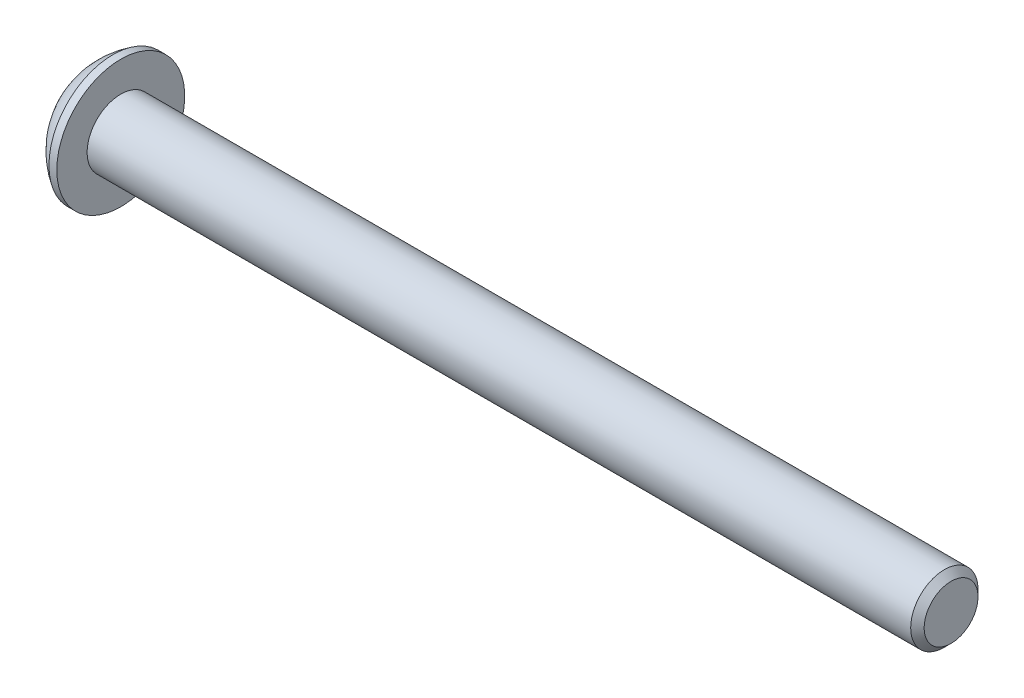
SolidWorks part; units mm, degrees
ref_plane "Front Plane" through (0, 0, 0) normal (0, 0, 1) x (1, 0, 0)
ref_plane "Top Plane" through (0, 0, 0) normal (0, 1, 0) x (1, 0, 0)
ref_plane "Right Plane" through (0, 0, 0) normal (1, 0, 0) x (0, 0, -1)
sketch "Sketch1" plane through (0, 0, 0) normal (0, 0, 1) x (1, 0, 0)
  line L0 (0, 0) -> (38.65, 0)
  line L1 (0, 0) -> (0, 1.43)
  line L2 (1.3, 2.85) -> (1.65, 2.85)
  line L3 (1.65, 2.85) -> (1.65, 1.5)
  line L4 (1.65, 1.5) -> (38.65, 1.5)
  line L5 (38.65, 1.5) -> (38.65, 0)
  arc A0 (0, 1.43) -> (1.3, 2.85) centre (3.132, -0.1322) cw
  dimension "D6" = 3.5
  dimension "D1" = 1.5
  dimension "D2" = 37
  dimension "D3" = 2.85
  dimension "D4" = 0.35
  dimension "D5" = 1.65
  dimension "D7" = 1.43
revolve "Revolve1" add sketch "Sketch1" angle 360 about L0
chamfer "Chamfer1" distance 0.3 angle 45 1 edges at (38.65, 0, 1.5)
sketch "Sketch2" plane through (0, 0, 0) normal (-1, 0, 0) x (0, 0, 1)
  line L1 (0, 1.1547) -> (-1, 0.5774)
  line L2 (-1, 0.5774) -> (-1, -0.5774)
  line L3 (-1, -0.5774) -> (0, -1.1547)
  line L4 (0, -1.1547) -> (1, -0.5774)
  line L5 (1, -0.5774) -> (1, 0.5774)
  line L6 (1, 0.5774) -> (0, 1.1547)
  circle A0 centre (0, 0) radius 1 construction
  dimension "D1" = 2
extrude "Cut-Extrude1" cut sketch "Sketch2" against normal blind 1
